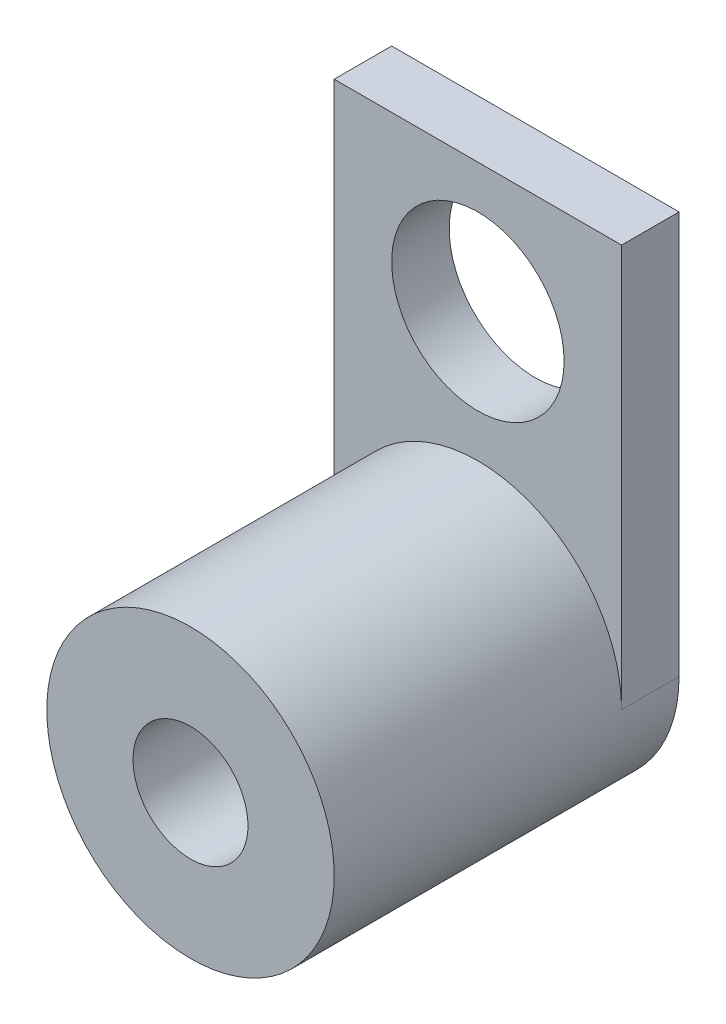
SolidWorks part; units mm, degrees
ref_plane "Front Plane" through (0, 0, 0) normal (1, 0, 0) x (0, 1, 0)
ref_plane "Top Plane" through (0, 0, 0) normal (0, 0, 1) x (0, 1, 0)
ref_plane "Right Plane" through (0, 0, 0) normal (0, 1, 0) x (-1, 0, 0)
sketch "Sketch3" plane through (0, 0, 0) normal (0, 0, 1) x (0, 1, 0)
  circle A0 centre (0, 0) radius 63.5
  circle A1 centre (0, 0) radius 25.4
  dimension "D1" = 127
  dimension "D2" = 50.8
extrude "Boss-Extrude1" add sketch "Sketch3" along normal blind 152.4
sketch "Sketch4" plane through (0, 0, 0) normal (0, 0, 1) x (0, 1, 0)
  line L1 (0, 63.5) -> (177.8, 63.5)
  line L2 (0, -63.5) -> (177.8, -63.5)
  line L3 (177.8, 63.5) -> (177.8, -63.5)
  line L4 (0, -55) -> (0, 55) construction
  line L5 (-55, 0) -> (55, 0) construction
  circle A0 centre (0, 0) radius 63.5 construction
  arc A1 (0, 63.5) -> (0, -63.5) centre (0, 0) ccw
  circle A2 centre (0, 0) radius 25.4 construction
  circle A3 centre (0, 0) radius 25.4
  circle A4 centre (120.65, 0) radius 38.1
  point P2 (0, 0)
  dimension "D2" = 76.2
  dimension "D1" = 177.8
  dimension "D3" = 57.15
extrude "Boss-Extrude2" add sketch "Sketch4" along normal blind 25.4
